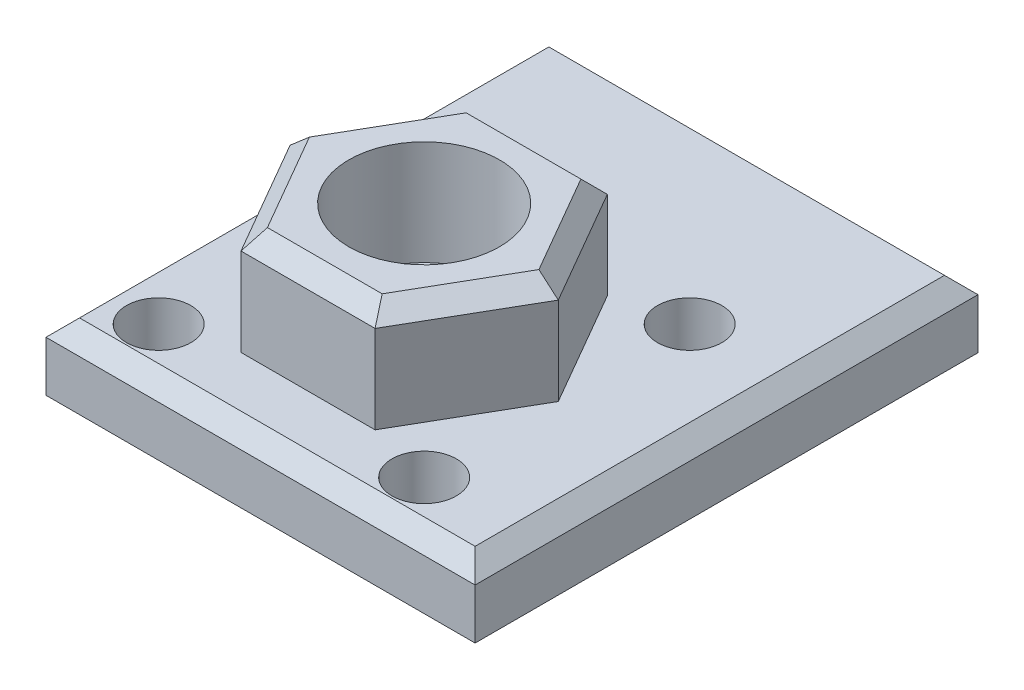
SolidWorks part; units mm, degrees
ref_plane "Front Plane" through (0, 0, 0) normal (0, 0, 1) x (1, 0, 0)
ref_plane "Top Plane" through (0, 0, 0) normal (0, 1, 0) x (1, 0, 0)
ref_plane "Right Plane" through (0, 0, 0) normal (1, 0, 0) x (0, 0, -1)
sketch "Sketch1" plane through (0, 0, 0) normal (0, 1, 0) x (1, 0, 0)
  line L3 (40.64, 13.335) -> (40.64, 60.96)
  line L4 (40.64, 60.96) -> (0, 60.96)
  line L6 (18.415, 30.734) -> (0, 0) construction
  line L7 (40.64, 13.335) -> (0, 13.335)
  line L8 (0, 60.96) -> (0, 13.335)
  circle A0 centre (18.415, 30.734) radius 2.3812 construction
  circle A1 centre (30.9874, 18.1616) radius 3.048
  circle A2 centre (30.9874, 43.3064) radius 3.048
  circle A3 centre (18.415, 30.734) radius 6.35 construction
  circle A4 centre (18.415, 30.734) radius 9.525 construction
  circle A5 centre (5.8426, 18.1616) radius 3.048
  circle A6 centre (5.8426, 43.3064) radius 3.048
  dimension "D5" = 6.096
  dimension "D1" = 13.335
  dimension "D2" = 40.64
  dimension "D3" = 47.625
  dimension "D6" = 25.1447
  dimension "D7" = 25.1447
extrude "Boss-Extrude1" add sketch "Sketch1" along normal blind 6.35
sketch "Sketch2" plane through (0, 6.35, 0) normal (0, 1, 0) x (1, 0, 0)
  line L7 (31.115, 30.734) -> (24.765, 41.7325)
  line L8 (24.765, 41.7325) -> (12.065, 41.7325)
  line L9 (12.065, 41.7325) -> (5.715, 30.734)
  line L10 (5.715, 30.734) -> (12.065, 19.7355)
  line L11 (12.065, 19.7355) -> (24.765, 19.7355)
  line L12 (24.765, 19.7355) -> (31.115, 30.734)
  circle A0 centre (18.415, 30.734) radius 10.9985 construction
  circle A5 centre (18.415, 30.734) radius 12.7 construction
  dimension "D2" = 25.4
extrude "Boss-Extrude2" add sketch "Sketch2" along normal blind 9.906
sketch "Sketch3" plane through (0, 16.256, 0) normal (0, 1, 0) x (1, 0, 0)
  circle A0 centre (18.415, 30.734) radius 4.826
  dimension "D1" = 9.652
extrude "Cut-Extrude1" cut sketch "Sketch3" against normal through all
sketch "Sketch4" plane through (0, 16.256, 0) normal (0, 1, 0) x (1, 0, 0)
  circle A0 centre (18.415, 30.734) radius 7.1374
  dimension "D1" = 14.2748
extrude "Cut-Extrude2" cut sketch "Sketch4" against normal blind 9.906
chamfer "Chamfer1" distance 1.5875 angle 45 10 edges at (0, 6.35, -37.1475) (20.32, 6.35, -60.96) (40.64, 6.35, -37.1475) (20.32, 6.35, -13.335) (18.415, 16.256, -19.7355) (8.89, 16.256, -25.2347) (8.89, 16.256, -36.2333) (18.415, 16.256, -41.7325) (27.94, 16.256, -36.2333) (27.94, 16.256, -25.2347)
